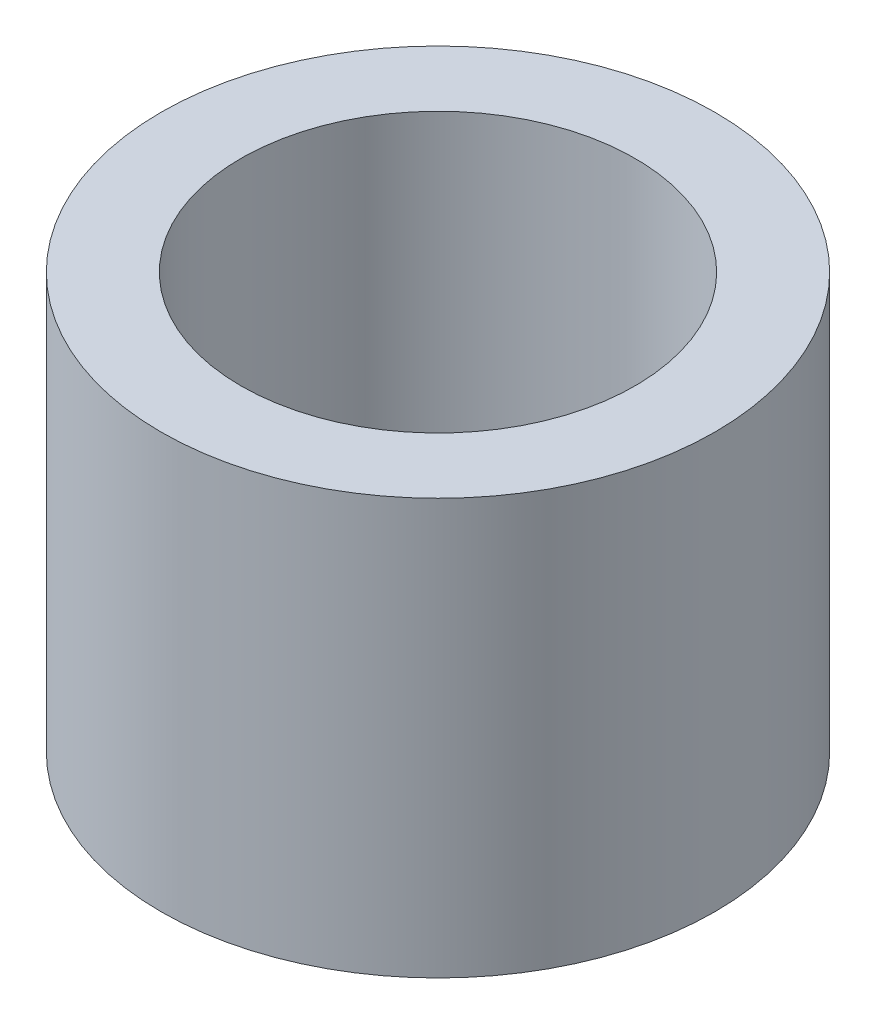
SolidWorks part; units mm, degrees
ref_plane "Alzado" through (0, 0, 0) normal (0, 0, 1) x (1, 0, 0)
ref_plane "Planta" through (0, 0, 0) normal (0, 1, 0) x (1, 0, 0)
ref_plane "Vista lateral" through (0, 0, 0) normal (1, 0, 0) x (0, 0, -1)
sketch "Croquis1" plane through (0, 0, 0) normal (0, 1, 0) x (1, 0, 0)
  circle A0 centre (0, 0) radius 35.575
  circle A1 centre (0, 0) radius 50
extrude "Saliente-Extruir3" add sketch "Croquis1" along normal blind 75 contours A1 | A0
